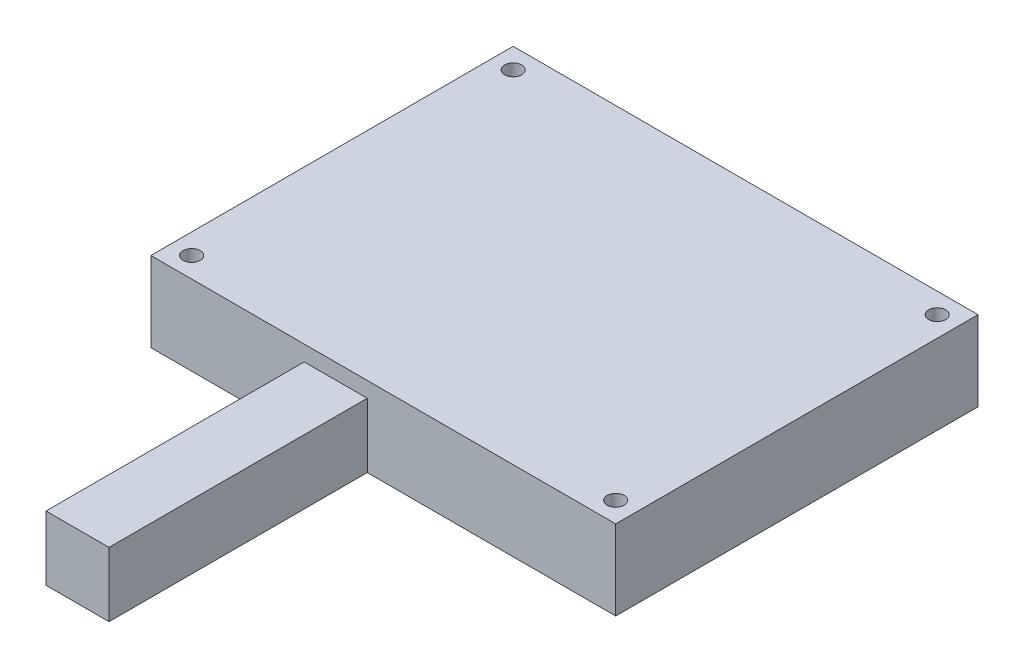
SolidWorks part; units mm, degrees
ref_plane "Front Plane" through (0, 0, 0) normal (0, 0, 1) x (1, 0, 0)
ref_plane "Top Plane" through (0, 0, 0) normal (0, 1, 0) x (1, 0, 0)
ref_plane "Right Plane" through (0, 0, 0) normal (1, 0, 0) x (0, 0, -1)
sketch "Sketch1" plane through (0, 0, 0) normal (0, 1, 0) x (1, 0, 0)
  line L0 (-45, 35.075) -> (-41.05, 35.075) construction
  line L1 (-45, -35.075) -> (45, -35.075)
  line L2 (-45, -35.075) -> (-45, 35.075)
  line L3 (-45, 35.075) -> (45, 35.075)
  line L4 (45, -35.075) -> (45, 35.075)
  line L5 (-45, -35.075) -> (45, 35.075) construction
  line L6 (-45, 35.075) -> (45, -35.075) construction
  line L7 (-41.05, 35.075) -> (-41.05, 31.125) construction
  line L8 (45, 35.075) -> (41.05, 35.075) construction
  line L9 (41.05, 35.075) -> (41.05, 31.125) construction
  line L10 (-41.05, -35.075) -> (-41.05, -31.125) construction
  line L11 (41.05, -35.075) -> (41.05, -31.125) construction
  circle A0 centre (-41.05, 31.125) radius 1.65
  circle A1 centre (41.05, 31.125) radius 1.65
  circle A2 centre (-41.05, -31.125) radius 1.65
  circle A3 centre (41.05, -31.125) radius 1.65
  point P0 (0, 0)
extrude "Boss-Extrude1" add sketch "Sketch1" along normal blind 15.45
sketch "Sketch2" plane through (0, 0, 35.075) normal (0, 0, 1) x (1, 0, 0)
  line L0 (-45, 0) -> (-15.3, 0) construction
  line L1 (-45, 0) -> (45, 0) construction
  line L2 (-15.3, 0) -> (-15.3, 12.46) construction
  line L3 (-15.3, 12.46) -> (-3.1, 12.46) construction
  line L5 (-15.3, 0) -> (-3.1, 0)
  line L6 (-15.3, 0) -> (-15.3, 12.46)
  line L7 (-15.3, 12.46) -> (-3.1, 12.46)
  line L8 (-3.1, 0) -> (-3.1, 12.46)
  line L9 (-15.3, 0) -> (-3.1, 12.46) construction
  line L10 (-15.3, 12.46) -> (-3.1, 0) construction
  point P9 (-9.2, 6.23)
extrude "Boss-Extrude2" add sketch "Sketch2" along normal blind 50
